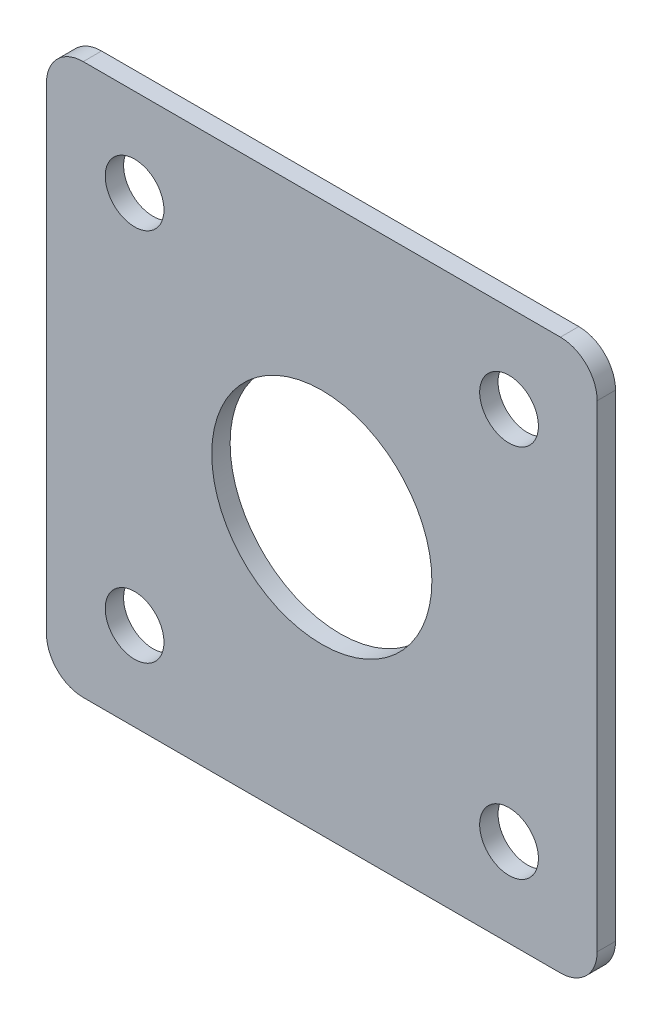
SolidWorks part; units mm, degrees
material "6061-O (SS)"
ref_plane "Front Plane" through (0, 0, 0) normal (0, 0, 1) x (1, 0, 0)
ref_plane "Top Plane" through (0, 0, 0) normal (0, 1, 0) x (1, 0, 0)
ref_plane "Right Plane" through (0, 0, 0) normal (1, 0, 0) x (0, 0, -1)
sketch "Sketch1" plane through (0, 0, 0) normal (0, 0, 1) x (1, 0, 0)
  line L1 (75, -75) -> (-75, -75)
  line L2 (75, -75) -> (75, 75)
  line L3 (75, 75) -> (-75, 75)
  line L4 (-75, -75) -> (-75, 75)
  line L5 (75, -75) -> (-75, 75) construction
  line L6 (75, 75) -> (-75, -75) construction
  line L7 (51, -51) -> (-51, -51) construction
  line L8 (51, -51) -> (51, 51) construction
  line L9 (51, 51) -> (-51, 51) construction
  line L10 (-51, -51) -> (-51, 51) construction
  line L11 (51, -51) -> (-51, 51) construction
  line L12 (51, 51) -> (-51, -51) construction
  circle A0 centre (0, 0) radius 29.98
  circle A1 centre (51, 51) radius 8
  circle A2 centre (-51, 51) radius 8
  circle A3 centre (-51, -51) radius 8
  circle A4 centre (51, -51) radius 8
  point P0 (0, 0)
  dimension "D3" = 59.96
  dimension "D4" = 16
  dimension "D1" = 150
  dimension "D2" = 150
  dimension "D5" = 102
  dimension "D6" = 102
extrude "Boss-Extrude1" add sketch "Sketch1" along normal blind 5
fillet "Fillet1" radius 10 4 edges at (75, -75, 2.5) (-75, -75, 2.5) (-75, 75, 2.5) (75, 75, 2.5)
